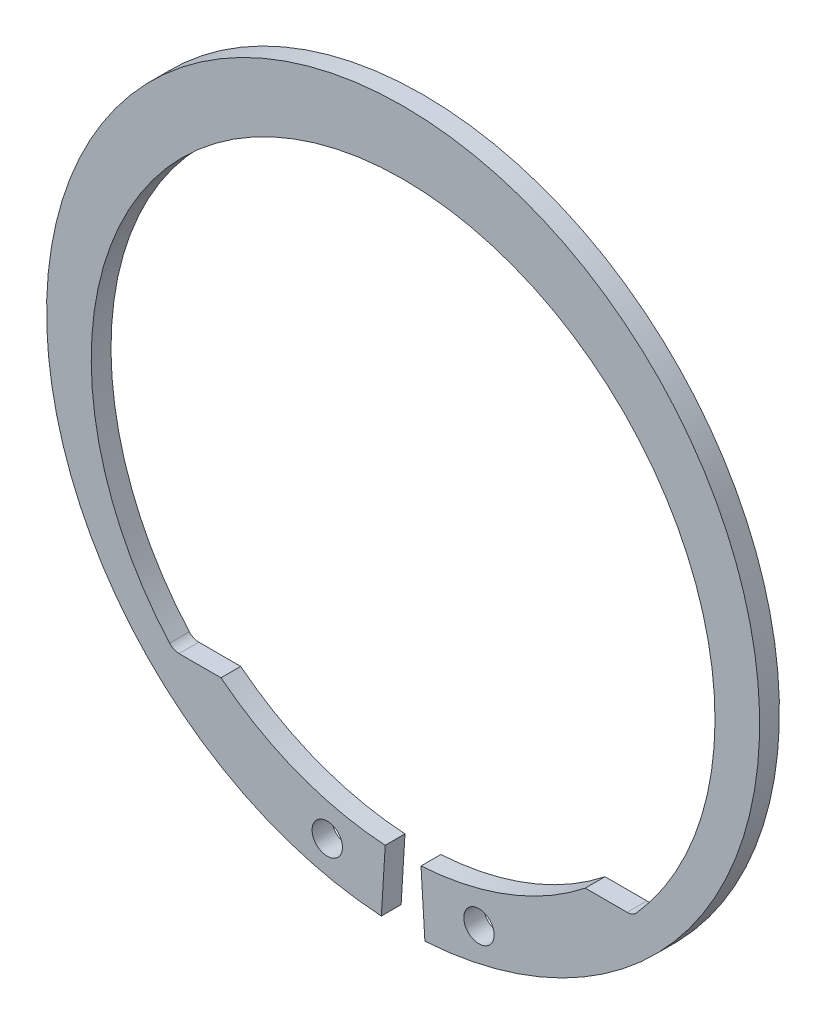
SolidWorks part; units mm, degrees
material "Alloy Steel"
ref_plane "Front" through (0, 0, 0) normal (0, 0, 1) x (1, 0, 0)
ref_plane "Top" through (0, 0, 0) normal (0, 1, 0) x (1, 0, 0)
ref_plane "Right" through (0, 0, 0) normal (1, 0, 0) x (0, 0, -1)
sketch "Sketch1" plane through (0, 0, 0) normal (0, 0, 1) x (1, 0, 0)
  line L1 (0, 35.7251) -> (0, -35.7251) construction
  line L2 (-18.2522, -23.0164) -> (-23.0164, -23.0164) construction
  line L4 (-23.0164, -23.0164) -> (-25.2615, -25.2615) construction
  line L5 (-23.0164, -23.0164) -> (0, 0) construction
  line L6 (0, 29.3751) -> (0, 35.7251) construction
  line L7 (0, 35.7251) -> (0, 32.5501) construction
  line L8 (0, -29.3751) -> (0, -26.342) construction
  line L9 (0, -29.3751) -> (0, -32.5501) construction
  line L10 (0, 0) -> (-2.181, -35.6585) construction
  line L11 (0, -32.5501) -> (0, -35.7251) construction
  line L12 (0, 0) -> (-7.5987, -31.6507) construction
  arc A0 (0, 35.7251) -> (-23.0164, -23.0164) centre (0, 1.8452) ccw construction
  circle A2 centre (0, 0) radius 35.7251 construction
  circle A4 centre (0, 0) radius 29.3751 construction
  circle A6 centre (-7.5987, -31.6507) radius 1.524 construction
  arc A7 (-7.5987, -31.6507) -> (-1.9871, -32.4894) centre (0, 0) ccw construction
  point P1 (0, 29.3751)
  dimension "D2" = 10
  dimension "Ring ID" = 58.7502
  dimension "Hole Diameter" = 3.048
  dimension "D4" = 45
  dimension "D6" = 3.5
  dimension "S Max " = 6.35
sketch "Sketch2" plane through (0, 0, 0) normal (0, 1, 0) x (1, 0, 0)
  line L0 (-35.7251, 0.9906) -> (-35.7251, -0.9906) construction
  point P3 (-35.7251, 0)
  dimension "Ring Thickness" = 1.9812
sketch "Sketch4" plane through (0, 0, 0) normal (0, 0, 1) x (1, 0, 0)
  line L1 (-18.2522, -23.0164) -> (-23.0164, -23.0164) construction
  line L2 (-18.2522, -23.0164) -> (-23.0164, -23.0164)
  line L3 (0, 0) -> (-2.181, -35.6585) construction
  line L5 (-1.7933, -29.3203) -> (-2.181, -35.6585)
  line L6 (0, 35.7251) -> (0, -35.7251) construction
  line L7 (0, 35.7251) -> (0, 29.3751)
  circle A2 centre (-7.5987, -31.6507) radius 1.524 construction
  arc A4 (-23.0164, -23.0164) -> (0, 29.3751) centre (0, -1.8764) cw
  circle A5 centre (0, 0) radius 29.3751 construction
  circle A6 centre (-7.5987, -31.6507) radius 1.524
  arc A8 (-18.2522, -23.0164) -> (-1.7933, -29.3203) centre (0, 0) ccw
  circle A9 centre (0, 0) radius 35.7251 construction
  arc A10 (0, 35.7251) -> (-2.181, -35.6585) centre (0, 0) ccw
extrude "Boss-Extrude1" add sketch "Sketch4" along normal mid plane 1.9812
fillet "Fillet1" radius 1.27 1 edges at (-23.0164, -23.0164, 0)
sketch "Sketch9" [suppressed] plane through (0, 0, 0) normal (0, 0, 1) x (1, 0, 0)
  line L0 (0, 0) -> (-11.6509, 20.1799) construction
  line L1 (-11.6509, 20.1799) -> (-11.9049, 20.6199)
  line L2 (0, 28.4861) -> (0, -28.4861) construction
  arc A1 (-11.6509, 20.1799) -> (-24.6421, 0) centre (0, -1.5922) ccw
  arc A2 (-11.9049, 20.6199) -> (-24.6421, 0) centre (1.1106, -1.664) ccw
  arc A5 (0, 23.1013) -> (-18.6277, -17.8026) centre (0, -1.5922) ccw construction
  dimension "D1" = 30
  dimension "D2" = 0.508
extrude "Cut-Extrude1" [suppressed] cut sketch "Sketch9" against normal through all both and the other way through all
fillet "Fillet2" [suppressed] radius 0.7937
mirror "Mirror1" about plane through (0, 0, 0) normal (1, 0, 0) of bodies 109
sketch "Sketch7" plane through (0, 0, 0) normal (0, 0, 1) x (1, 0, 0)
  arc A0 (23.4026, -22.5881) -> (-23.4026, -22.5881) centre (0, -1.8764) ccw construction
  point P0 (-31.1951, 0)
equation "\"D1@Boss-Extrude1\" = \"Ring Thickness@Sketch2\""
